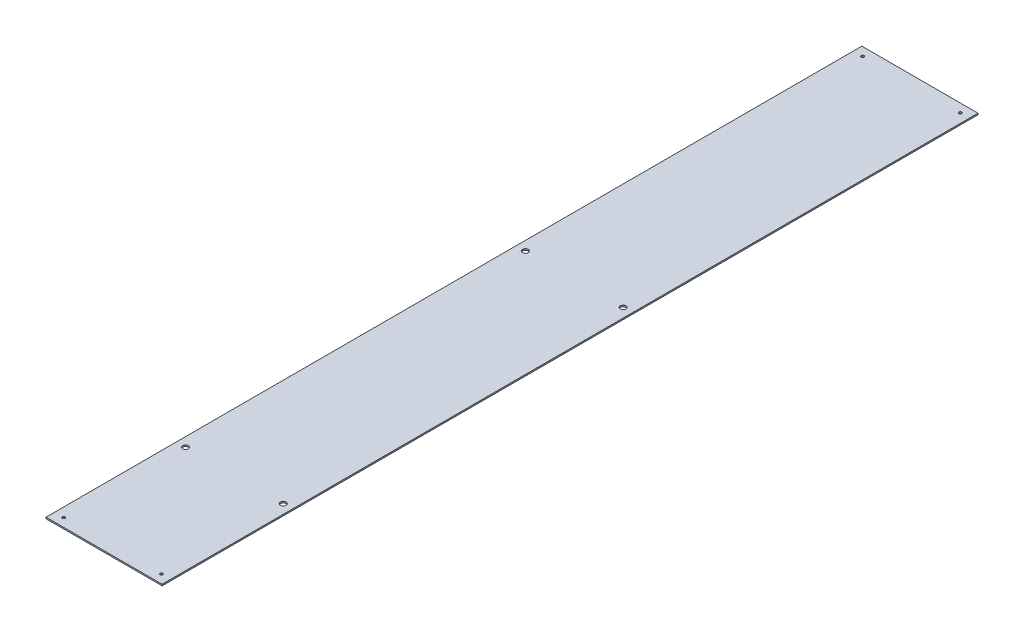
SolidWorks part; units mm, degrees
material "Balsa"
ref_plane "Front Plane" through (0, 0, 0) normal (0, 0, 1) x (1, 0, 0)
ref_plane "Top Plane" through (0, 0, 0) normal (0, 1, 0) x (1, 0, 0)
ref_plane "Right Plane" through (0, 0, 0) normal (1, 0, 0) x (0, 0, -1)
sketch "Sketch1" plane through (0, 0, 0) normal (0, 1, 0) x (1, 0, 0)
  line L1 (-65.0875, -457.2) -> (65.0875, -457.2)
  line L2 (-65.0875, -457.2) -> (-65.0875, 457.2)
  line L3 (-65.0875, 457.2) -> (65.0875, 457.2)
  line L4 (65.0875, -457.2) -> (65.0875, 457.2)
  line L5 (-65.0875, -457.2) -> (65.0875, 457.2) construction
  line L6 (-65.0875, 457.2) -> (65.0875, -457.2) construction
  point P0 (0, 0)
  dimension "D1" = 914.4
  dimension "D2" = 130.175
extrude "Boss-Extrude1" add sketch "Sketch1" against normal blind 1.5875
sketch "Sketch2" plane through (0, 0, 0) normal (0, 1, 0) x (1, 0, 0)
  line L0 (54.7687, -457.2) -> (54.7687, 457.2) construction
  line L1 (-65.0875, -457.2) -> (65.0875, -457.2) construction
  line L2 (65.0875, 457.2) -> (-65.0875, 457.2) construction
  line L3 (65.0875, -457.2) -> (65.0875, 457.2) construction
  circle A0 centre (54.7687, -447.675) radius 1.5875
  circle A1 centre (54.7687, -311.15) radius 3.175
  circle A2 centre (54.7687, 447.675) radius 1.5875
  circle A3 centre (54.7687, 69.85) radius 3.175
  dimension "D4" = 3.175
  dimension "D5" = 6.35
  dimension "D8" = 3.175
  dimension "D9" = 6.35
  dimension "D1" = 10.3187
  dimension "D2" = 9.525
  dimension "D3" = 136.525
  dimension "D6" = 9.525
  dimension "D7" = 381
extrude "Cut-Extrude2" cut sketch "Sketch2" against normal through all
ref_plane "Plane1" through (0, 0, 0) normal (1, 0, 0) x (0, 0, -1)
mirror "Mirror2" about plane through (0, 0, 0) normal (1, 0, 0) of "Cut-Extrude2"
